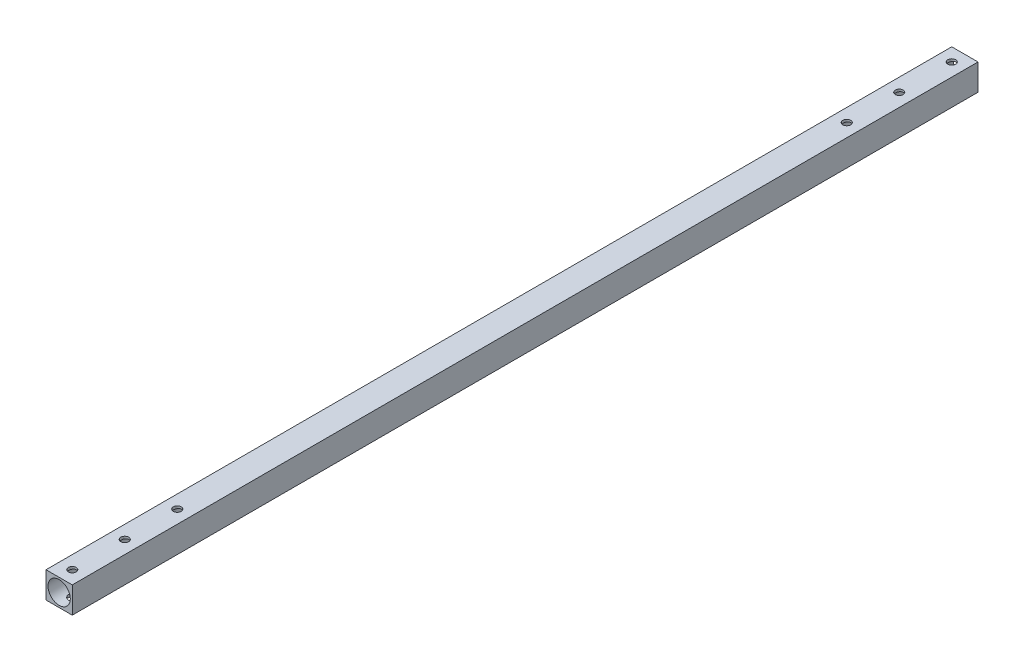
SolidWorks part; units mm, degrees
material "Thornel VCB-20 Carbon Cloth"
ref_plane "Front Plane" through (0, 0, 0) normal (0, 0, 1) x (1, 0, 0)
ref_plane "Top Plane" through (0, 0, 0) normal (0, 1, 0) x (1, 0, 0)
ref_plane "Right Plane" through (0, 0, 0) normal (1, 0, 0) x (0, 0, -1)
sketch "Sketch1" plane through (0, 0, 0) normal (0, 0, 1) x (1, 0, 0)
  line L1 (-5, -5) -> (5, -5)
  line L2 (-5, -5) -> (-5, 5)
  line L3 (-5, 5) -> (5, 5)
  line L4 (5, -5) -> (5, 5)
  line L5 (-5, -5) -> (5, 5) construction
  line L6 (-5, 5) -> (5, -5) construction
  circle A0 centre (0, 0) radius 4.25
  point P0 (0, 0)
  dimension "D3" = 8.5
  dimension "D1" = 10
  dimension "D2" = 10
extrude "Boss-Extrude1" add sketch "Sketch1" along normal blind 345
sketch "Sketch2" plane through (0, 5, 0) normal (0, 1, 0) x (1, 0, 0)
  line L0 (0, 0) -> (0, -5) construction
  line L1 (0, -5) -> (0, -25) construction
  line L2 (0, -25) -> (0, -45) construction
  line L3 (0, -345) -> (0, -340) construction
  line L4 (5, -345) -> (-5, -345) construction
  line L5 (0, -340) -> (0, -320) construction
  line L6 (0, -320) -> (0, -300) construction
  circle A0 centre (0, -5) radius 1.5
  circle A1 centre (0, -25) radius 1.5
  circle A2 centre (0, -45) radius 1.5
  circle A3 centre (0, -340) radius 1.5
  circle A4 centre (0, -320) radius 1.5
  circle A5 centre (0, -300) radius 1.5
  dimension "D3" = 3
  dimension "D4" = 5
  dimension "D6" = 3
  dimension "D1" = 5
  dimension "D2" = 20
  dimension "D5" = 20
extrude "Cut-Extrude1" cut sketch "Sketch2" against normal through all
